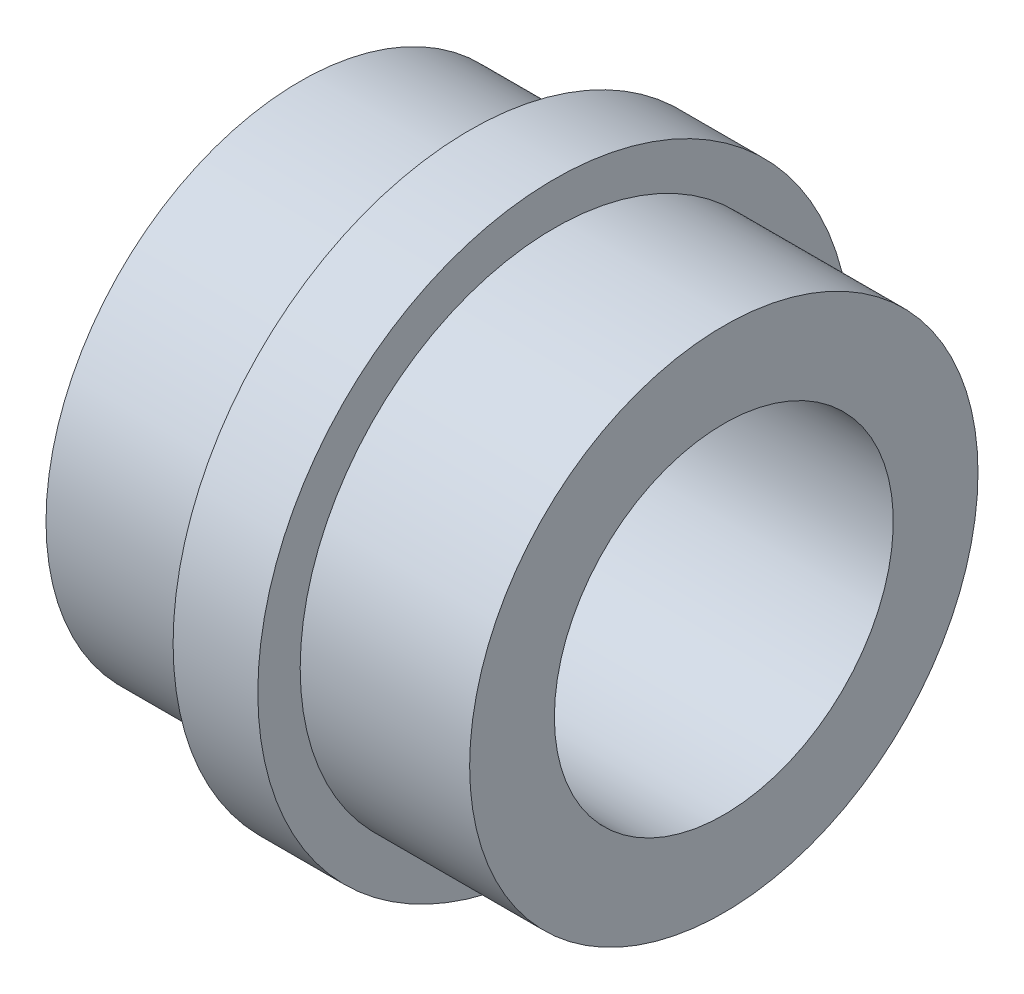
SolidWorks part; units mm, degrees
material "Copper"
ref_plane "Front Plane" through (0, 0, 0) normal (0, 0, 1) x (1, 0, 0)
ref_plane "Top Plane" through (0, 0, 0) normal (0, 1, 0) x (1, 0, 0)
ref_plane "Right Plane" through (0, 0, 0) normal (1, 0, 0) x (0, 0, -1)
sketch "Sketch2" plane through (0, 0, 0) normal (0, 1, 0) x (1, 0, 0)
  line L0 (0, 0) -> (50, 0)
  line L1 (30, 30) -> (50, 30)
  line L2 (0, 20) -> (50, 20)
  line L3 (0, 20) -> (0, 30)
  line L4 (0, 30) -> (20, 30)
  line L5 (50, 20) -> (50, 30)
  line L7 (20, 30) -> (20, 35)
  line L8 (20, 35) -> (30, 35)
  line L9 (30, 30) -> (30, 35)
  dimension "D1" = 20
  dimension "D2" = 50
  dimension "D3" = 50
  dimension "D4" = 10
  dimension "D5" = 5
  dimension "D6" = 10
  dimension "D7" = 20
  dimension "D8" = 15
revolve "Revolve1" add sketch "Sketch2" angle 360 about L0
